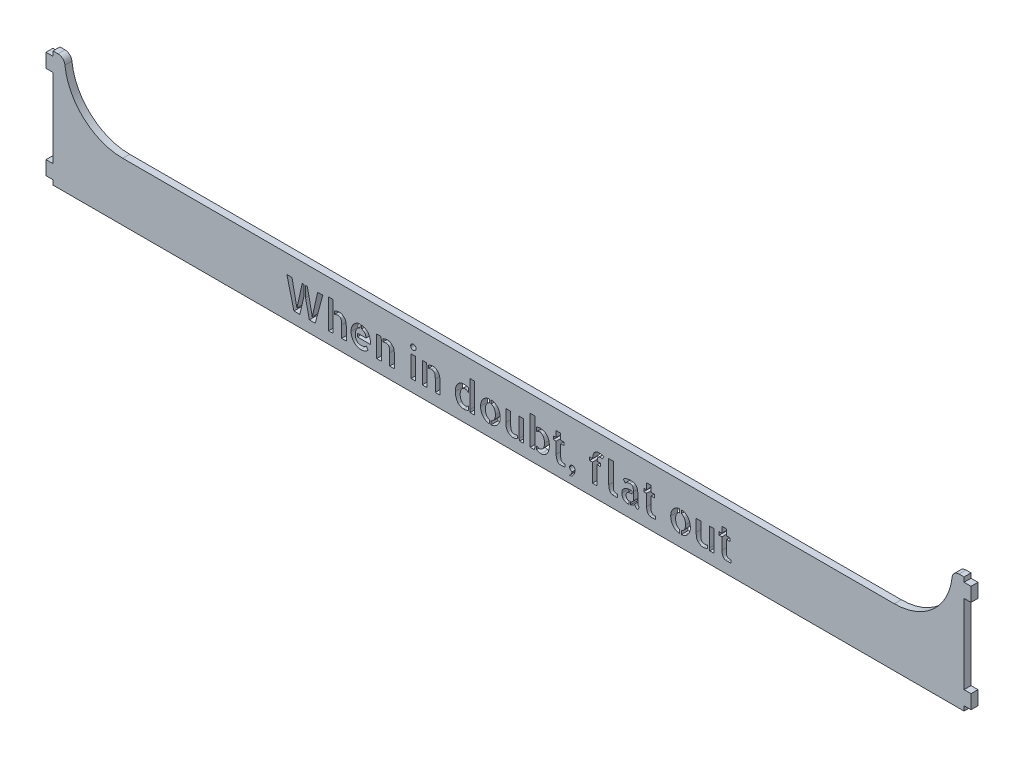
SolidWorks part; units mm, degrees
ref_plane "Front Plane" through (0, 0, 0) normal (0, 0, 1) x (1, 0, 0)
ref_plane "Top Plane" through (0, 0, 0) normal (0, 1, 0) x (1, 0, 0)
ref_plane "Right Plane" through (0, 0, 0) normal (1, 0, 0) x (0, 0, -1)
sketch "Sketch1" plane through (0, 0, 0) normal (0, 0, 1) x (1, 0, 0)
  line L0 (-196, 0) -> (196, 0)
  line L1 (-199, 25) -> (199, 25)
  line L2 (-199, 25) -> (-199, -25)
  line L3 (-199, -25) -> (199, -25)
  line L4 (199, 25) -> (199, -25)
  line L5 (-199, 25) -> (199, -25) construction
  line L6 (-199, -25) -> (199, 25) construction
  line L7 (196, -25) -> (-196, -25)
  line L8 (196, -25) -> (196, 25)
  line L9 (196, 25) -> (-196, 25)
  line L10 (-196, -25) -> (-196, 25)
  line L11 (196, -25) -> (-196, 25) construction
  line L12 (196, 25) -> (-196, -25) construction
  line L13 (0, 25) -> (0, -25) construction
  line L14 (-197.5, 23) -> (-197.5, 25) construction
  line L15 (-199, -23) -> (-196, -23)
  line L16 (-199, -23) -> (-199, -17)
  line L17 (-199, -17) -> (-196, -17)
  line L18 (-196, -23) -> (-196, -17)
  line L19 (-199, 17) -> (-196, 17)
  line L20 (-199, 17) -> (-199, 23)
  line L21 (-199, 23) -> (-196, 23)
  line L22 (-196, 17) -> (-196, 23)
  line L23 (-197.5, -23) -> (-197.5, -25) construction
  line L24 (-197.5, 23) -> (-197.5, 17) construction
  line L25 (-197.5, -23) -> (-197.5, -17) construction
  line L26 (199, -23) -> (196, -23)
  line L27 (199, -17) -> (196, -17)
  line L28 (199, 17) -> (196, 17)
  line L29 (199, 23) -> (196, 23)
  line L30 (-191, 25) -> (-191, -25) construction
  arc A0 (-191, 25) -> (-166, 0) centre (-166, 25) ccw
  arc A1 (191, 25) -> (166, 0) centre (166, 25) cw
  point P0 (0, 0)
  point P6 (0, 0)
  dimension "D1" = 398
  dimension "D2" = 50
  dimension "D3" = 3
  dimension "D4" = 2
  dimension "D5" = 6
  dimension "D6" = 5
extrude "Boss-Extrude1" add sketch "Sketch1" along normal blind 3 contours L21 L2 L19 L10 | A0 L1 L10 L0 | L10 L3 L8 L0 | L17 L2 L15 L10 | L4 L27 L8 L26 | L1 A1 L0 L8 | L4 L29 L8 L28
fillet "Fillet1" radius 3 2 edges at (191, 25, 1.5) (-191, 25, 1.5)
sketch "Sketch2" plane through (0, 0, 3) normal (0, 0, 1) x (1, 0, 0)
  line L0 (-199, -20) -> (199, -20) construction
  line L1 (-199, -17) -> (-199, -23) construction
  line L2 (199, -17) -> (199, -23) construction
  text T0 "When in doubt, flat out" font "Allerta Stencil" height 12
  point P3 (0, 0)
  point P6 (0, 0)
extrude "Cut-Extrude1" cut sketch "Sketch2" against normal up to next (3 mm away)
